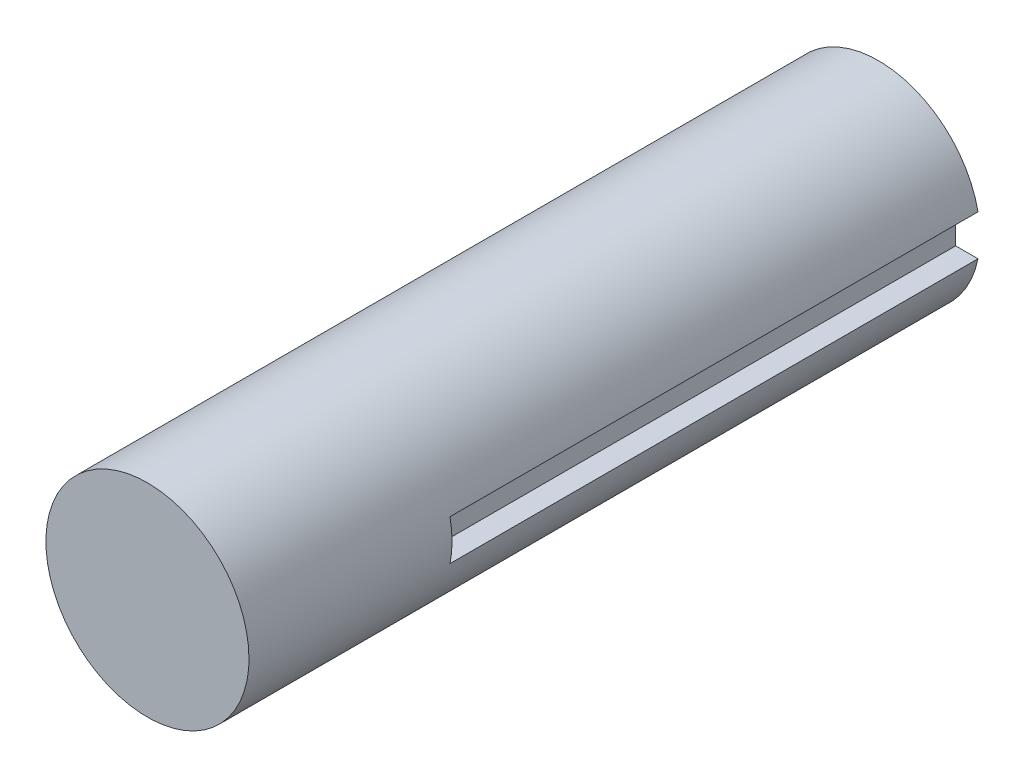
SolidWorks part; units mm, degrees
material "AISI 1045 Steel, cold drawn"
ref_plane "Front Plane" through (0, 0, 0) normal (0, 0, 1) x (1, 0, 0)
ref_plane "Top Plane" through (0, 0, 0) normal (0, 1, 0) x (1, 0, 0)
ref_plane "Right Plane" through (0, 0, 0) normal (1, 0, 0) x (0, 0, -1)
sketch "Sketch2" plane through (0, 0, 0) normal (0, 0, 1) x (1, 0, 0)
  circle A0 centre (0, 0) radius 50
  dimension "D1" = 100
extrude "Boss-Extrude1" add sketch "Sketch2" along normal blind 360
sketch "Sketch3" plane through (0, 0, 0) normal (0, 0, 1) x (1, 0, 0)
  line L0 (-61.3399, 0) -> (61.3399, 0) construction
  line L1 (48.9898, 10) -> (37.9798, 10)
  line L2 (37.9798, 10) -> (37.9798, -10)
  line L3 (37.9798, -10) -> (48.9898, -10)
  circle A0 centre (0, 0) radius 50 construction
  arc A1 (48.9898, -10) -> (48.9898, 10) centre (0, 0) ccw
  point P4 (0, 0)
  point P9 (37.9798, 0)
  dimension "D4" = 100
  dimension "D1" = 0
  dimension "D2" = 20
  dimension "D3" = 11.01
extrude "Cut-Extrude2" cut sketch "Sketch3" along normal blind 260 contours L2 L3 A1 L1
